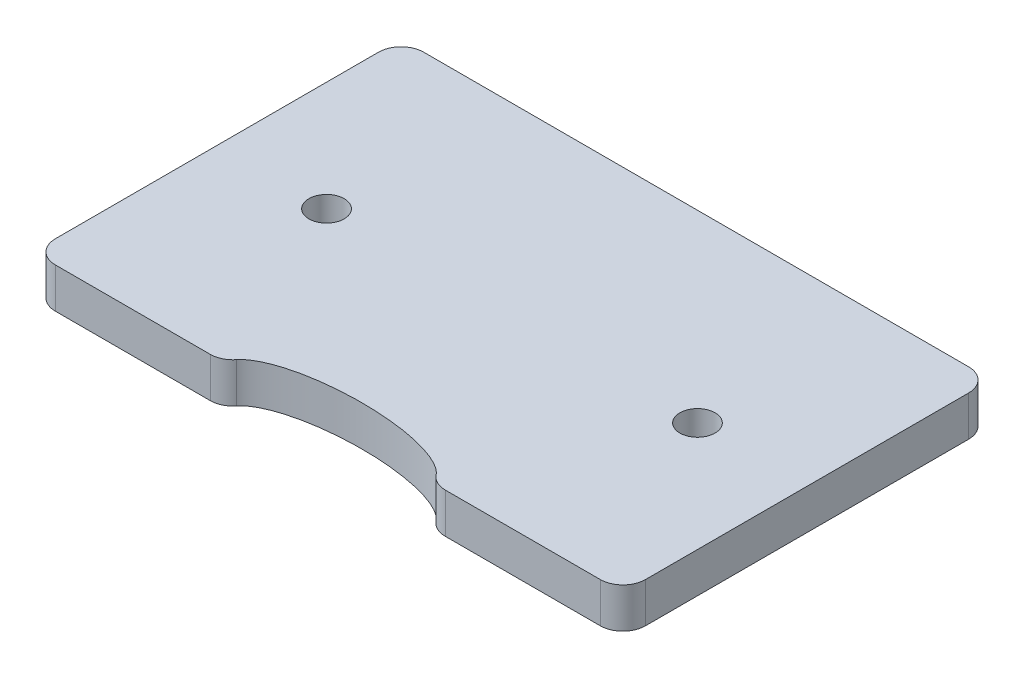
SolidWorks part; units mm, degrees
ref_plane "Front Plane" through (0, 0, 0) normal (0, 0, 1) x (1, 0, 0)
ref_plane "Top Plane" through (0, 0, 0) normal (0, 1, 0) x (1, 0, 0)
ref_plane "Right Plane" through (0, 0, 0) normal (1, 0, 0) x (0, 0, -1)
sketch "Sketch1" plane through (0, 0, 0) normal (0, 1, 0) x (1, 0, 0)
  line L0 (0, 0) -> (-20.8153, 0) construction
  line L1 (30.5816, 20.675) -> (-30.5816, 20.675)
  line L2 (33.1216, 18.135) -> (33.1216, -18.135)
  line L3 (30.5816, -20.675) -> (13.1872, -20.675)
  line L4 (-33.1216, 18.135) -> (-33.1216, -18.135)
  line L5 (33.1216, 20.675) -> (-33.1216, -20.675) construction
  line L6 (33.1216, -20.675) -> (-33.1216, 20.675) construction
  line L7 (0, 0) -> (0, 20.675) construction
  line L8 (-13.1872, -20.675) -> (-30.5816, -20.675)
  circle A0 centre (-20.8153, 0) radius 1.975
  circle A1 centre (20.8153, 0) radius 1.975
  arc A2 (33.1216, -18.135) -> (30.5816, -20.675) centre (30.5816, -18.135) cw
  arc A3 (-30.5816, -20.675) -> (-33.1216, -18.135) centre (-30.5816, -18.135) cw
  arc A4 (30.5816, 20.675) -> (33.1216, 18.135) centre (30.5816, 18.135) cw
  arc A5 (-30.5816, 20.675) -> (-33.1216, 18.135) centre (-30.5816, 18.135) ccw
  arc A6 (13.1872, -20.675) -> (11.1968, -19.7128) centre (13.1872, -18.135) cw
  arc A7 (-13.1872, -20.675) -> (-11.1968, -19.7128) centre (-13.1872, -18.135) ccw
  ellipse E0 centre (0, -20.675) end of major axis (-11.5718, -20.675) minor radius 3.81 (11.1968, -19.7128) -> (-11.1968, -19.7128) ccw
  point P1 (0, 0)
  dimension "D4" = 3.95
  dimension "D5" = 2.54
  dimension "D8" = 2.54
  dimension "D1" = 41.35
  dimension "D2" = 66.2432
  dimension "D3" = 20.8153
  dimension "D6" = 3.81
  dimension "D7" = 11.5718
extrude "Boss-Extrude1" add sketch "Sketch1" along normal blind 4.5
